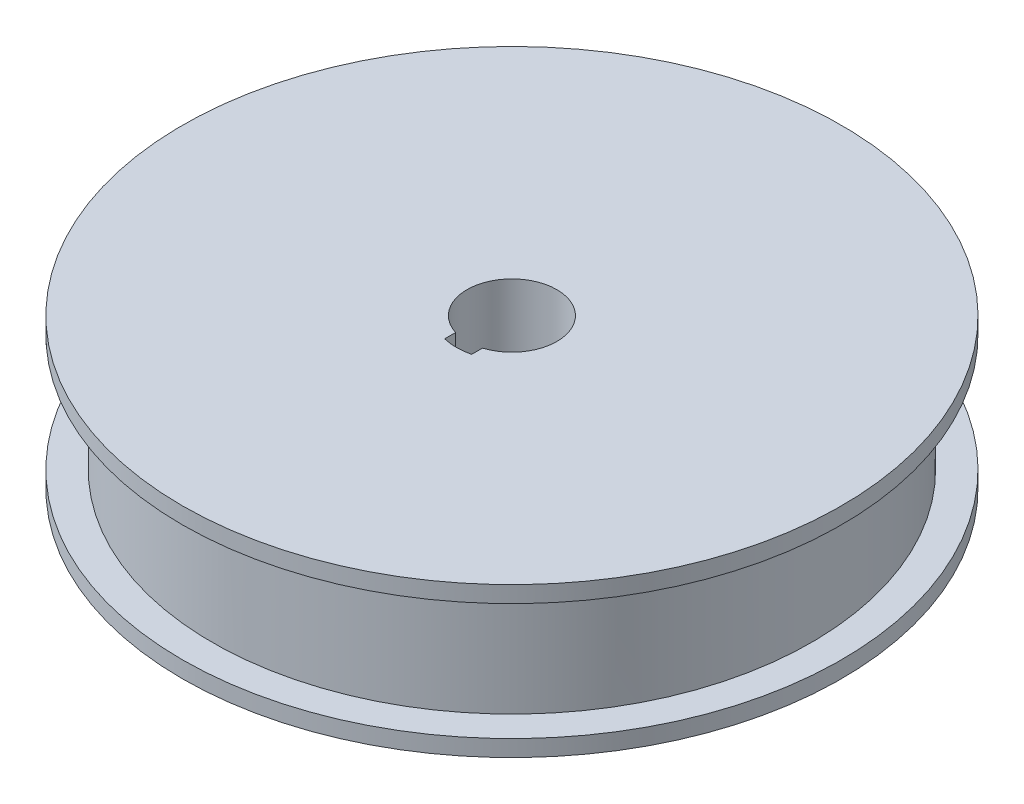
SolidWorks part; units mm, degrees
ref_plane "Front Plane" through (0, 0, 0) normal (0, 0, 1) x (1, 0, 0)
ref_plane "Top Plane" through (0, 0, 0) normal (0, 1, 0) x (1, 0, 0)
ref_plane "Right Plane" through (0, 0, 0) normal (1, 0, 0) x (0, 0, -1)
sketch "Sketch1" plane through (0, 0, 0) normal (0, 1, 0) x (1, 0, 0)
  circle A0 centre (0, 0) radius 200
  circle A1 centre (0, 0) radius 30
  dimension "D1" = 60
  dimension "D2" = 400
extrude "Boss-Extrude1" add sketch "Sketch1" along normal mid plane 100
sketch "Sketch2" plane through (0, 50, 0) normal (0, 1, 0) x (1, 0, 0)
  circle A0 centre (0, 0) radius 30 construction
  circle A1 centre (0, 0) radius 30
  circle A4 centre (0, 0) radius 220
  circle A5 centre (0, 0) radius 220
  dimension "D1" = 20
extrude "Boss-Extrude2" add sketch "Sketch2" against normal blind 11
mirror "Mirror1" about plane through (0, 0, 0) normal (0, 1, 0) of "Boss-Extrude2"
sketch "Sketch3" plane through (0, -50, 0) normal (0, -1, 0) x (1, 0, 0)
  line L0 (0, 22.8524) -> (0, 37) construction
  line L1 (-9, 35.8887) -> (-9, 22.8524)
  line L2 (9, 35.8887) -> (9, 22.8524)
  line L3 (-9, 22.8524) -> (9, 22.8524)
  circle A4 centre (0, 0) radius 37
  arc A5 (9, 35.8887) -> (-9, 35.8887) centre (0, 0) ccw
  dimension "D2" = 9
  dimension "D1" = 7
extrude "Cut-Extrude1" cut sketch "Sketch3" against normal through all
